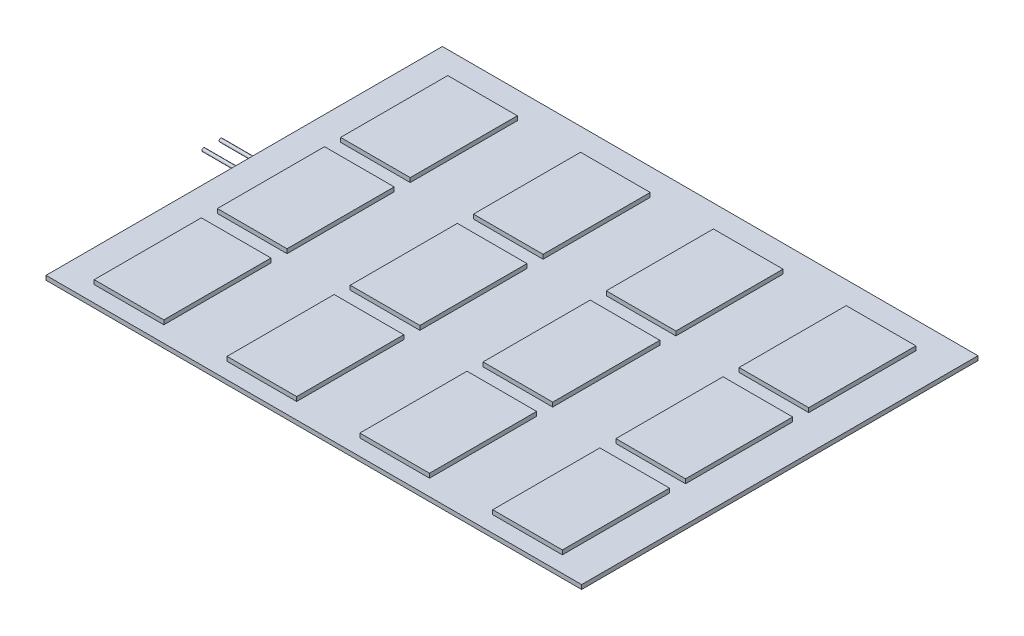
SolidWorks part; units mm, degrees
ref_plane "Front Plane" through (0, 0, 0) normal (0, 0, 1) x (1, 0, 0)
ref_plane "Top Plane" through (0, 0, 0) normal (0, 1, 0) x (1, 0, 0)
ref_plane "Right Plane" through (0, 0, 0) normal (1, 0, 0) x (0, 0, -1)
sketch "Sketch1" plane through (0, 0, 0) normal (0, 1, 0) x (1, 0, 0)
  line L1 (-250, 185) -> (250, 185)
  line L2 (-250, 185) -> (-250, -185)
  line L3 (-250, -185) -> (250, -185)
  line L4 (250, 185) -> (250, -185)
  line L5 (-250, 185) -> (250, -185) construction
  line L6 (-250, -185) -> (250, 185) construction
  point P0 (0, 0)
  dimension "D1" = 500
  dimension "D2" = 370
extrude "panel_base" add sketch "Sketch1" along normal blind 4
sketch "Sketch2" plane through (0, 4, 0) normal (0, 1, 0) x (1, 0, 0)
  line L0 (-250, 185) -> (-250, -185) construction
  line L1 (-220, 160) -> (-155, 160)
  line L2 (-220, 160) -> (-220, 60)
  line L3 (-220, 60) -> (-155, 60)
  line L4 (-155, 160) -> (-155, 60)
  line L5 (250, 185) -> (-250, 185) construction
  dimension "D1" = 100
  dimension "D2" = 65
  dimension "D3" = 30
  dimension "D4" = 25
extrude "solar_array" add sketch "Sketch2" along normal blind 4
pattern_linear "LPattern1" count 4 spacing 124 along (1, 0, 0) count 3 spacing 115 along (0, 0, 1) of "solar_array"
sketch "Sketch3" plane through (-250, 0, 0) normal (-1, 0, 0) x (0, 0, 1)
  circle A0 centre (-8, 1.9303) radius 1.5
  dimension "D1" = 3
  dimension "D3" = 8
extrude "positive_wire" add sketch "Sketch3" along normal blind 30
sketch "Sketch4" plane through (-250, 0, 0) normal (-1, 0, 0) x (0, 0, 1)
  circle A1 centre (8, 2.1463) radius 1.5
  dimension "D1" = 3
  dimension "D2" = 8
extrude "negative_wire" add sketch "Sketch4" along normal blind 30
